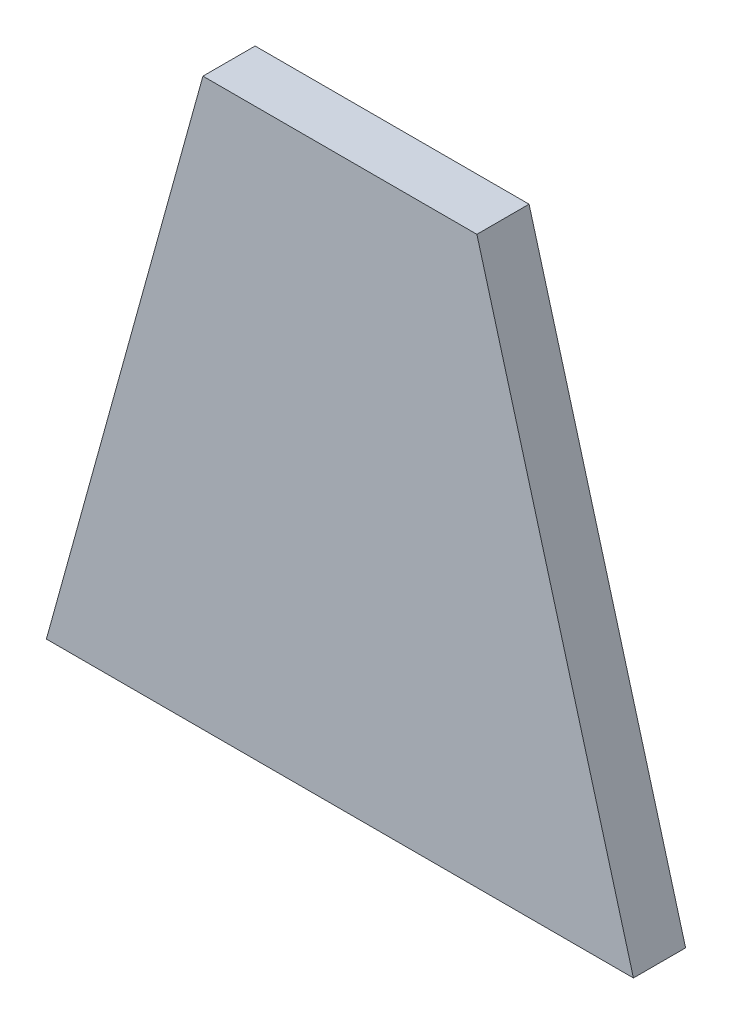
SolidWorks part; units mm, degrees
ref_plane "Front Plane" through (0, 0, 0) normal (0, 0, 1) x (1, 0, 0)
ref_plane "Top Plane" through (0, 0, 0) normal (0, 1, 0) x (1, 0, 0)
ref_plane "Right Plane" through (0, 0, 0) normal (1, 0, 0) x (0, 0, -1)
sketch "Sketch1" plane through (0, 0, 0) normal (0, 0, 1) x (1, 0, 0)
  line L0 (0, 0) -> (12, 43.3705)
  line L1 (12, 43.3705) -> (33, 43.3705)
  line L2 (33, 43.3705) -> (45, 0)
  line L3 (45, 0) -> (0, 0)
  dimension "D1" = 21
  dimension "D2" = 45
  dimension "D3" = 45
  dimension "D4" = 45
extrude "Boss-Extrude1" add sketch "Sketch1" along normal blind 4
